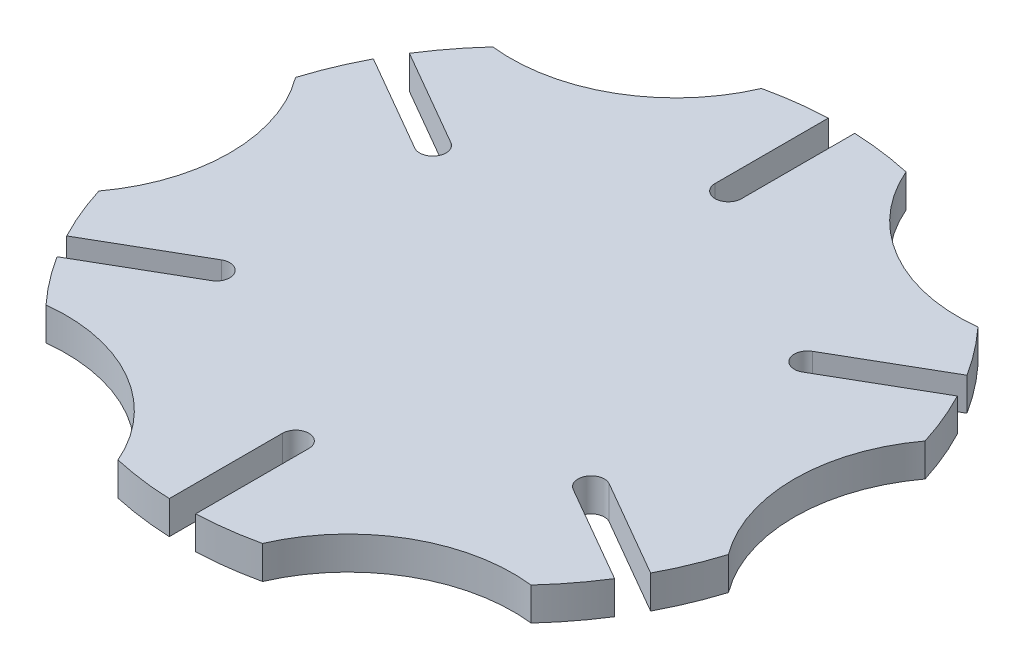
SolidWorks part; units mm, degrees
ref_plane "Front Plane" through (0, 0, 0) normal (0, 0, 1) x (1, 0, 0)
ref_plane "Top Plane" through (0, 0, 0) normal (0, 1, 0) x (1, 0, 0)
ref_plane "Right Plane" through (0, 0, 0) normal (1, 0, 0) x (0, 0, -1)
sketch "Sketch1" plane through (0, 0, 0) normal (0, 1, 0) x (1, 0, 0)
  line L0 (0, 0) -> (43.3013, 25) construction
  line L1 (43.3013, 25) -> (67.7962, 0) construction
  line L2 (67.7962, 0) -> (0, 0) construction
  line L3 (43.3013, 25) -> (28.4023, 16.3981) construction
  line L4 (44.3013, 23.2679) -> (29.4023, 14.666)
  line L5 (42.3013, 26.7321) -> (27.4023, 18.1301)
  line L6 (43.3013, -25) -> (28.4023, -16.3981) construction
  line L7 (42.3013, -26.7321) -> (27.4023, -18.1301)
  line L8 (44.3013, -23.2679) -> (29.4023, -14.666)
  line L9 (0, -50) -> (0, -32.7962) construction
  line L10 (-2, -50) -> (-2, -32.7962)
  line L11 (2, -50) -> (2, -32.7962)
  line L12 (-43.3013, -25) -> (-28.4023, -16.3981) construction
  line L13 (-44.3013, -23.2679) -> (-29.4023, -14.666)
  line L14 (-42.3013, -26.7321) -> (-27.4023, -18.1301)
  line L15 (-43.3013, 25) -> (-28.4023, 16.3981) construction
  line L16 (-42.3013, 26.7321) -> (-27.4023, 18.1301)
  line L17 (-44.3013, 23.2679) -> (-29.4023, 14.666)
  line L18 (0, 50) -> (0, 32.7962) construction
  line L19 (2, 50) -> (2, 32.7962)
  line L20 (-2, 50) -> (-2, 32.7962)
  circle A0 centre (67.7962, 0) radius 35
  circle A1 centre (0, 0) radius 32.7962 construction
  circle A2 centre (0, 0) radius 50
  arc A3 (44.3013, 23.2679) -> (42.3013, 26.7321) centre (43.3013, 25) ccw
  arc A4 (27.4023, 18.1301) -> (29.4023, 14.666) centre (28.4023, 16.3981) ccw
  circle A5 centre (67.7962, 0) radius 25
  arc A6 (48.0582, 14.8493) -> (48.0582, -14.8493) centre (67.7962, 0) cw
  arc A7 (48.0582, -14.8493) -> (48.0582, 14.8493) centre (0, 0) ccw
  circle A8 centre (33.8981, -58.7132) radius 25
  arc A9 (42.3013, -26.7321) -> (44.3013, -23.2679) centre (43.3013, -25) ccw
  arc A10 (29.4023, -14.666) -> (27.4023, -18.1301) centre (28.4023, -16.3981) ccw
  circle A11 centre (-33.8981, -58.7132) radius 25
  arc A12 (-2, -50) -> (2, -50) centre (0, -50) ccw
  arc A13 (2, -32.7962) -> (-2, -32.7962) centre (0, -32.7962) ccw
  circle A14 centre (-67.7962, 0) radius 25
  arc A15 (-44.3013, -23.2679) -> (-42.3013, -26.7321) centre (-43.3013, -25) ccw
  arc A16 (-27.4023, -18.1301) -> (-29.4023, -14.666) centre (-28.4023, -16.3981) ccw
  circle A17 centre (-33.8981, 58.7132) radius 25
  arc A18 (-42.3013, 26.7321) -> (-44.3013, 23.2679) centre (-43.3013, 25) ccw
  arc A19 (-29.4023, 14.666) -> (-27.4023, 18.1301) centre (-28.4023, 16.3981) ccw
  circle A20 centre (33.8981, 58.7132) radius 25
  arc A21 (2, 50) -> (-2, 50) centre (0, 50) ccw
  arc A22 (-2, 32.7962) -> (2, 32.7962) centre (0, 32.7962) ccw
  point P7 (35.8518, 20.699)
  point P16 (-44.2689, 68.1975)
  point P17 (0, 0)
  point P18 (0, 0)
  point P21 (35.8518, -20.699)
  point P30 (0, -41.3981)
  point P39 (-35.8518, -20.699)
  point P48 (-35.8518, 20.699)
  point P57 (0, 41.3981)
  point P64 (0, 0)
  dimension "D4" = 2
  dimension "D5" = 50
  dimension "D6" = 0.3
  dimension "D7" = 0.3
  dimension "D8" = 6
  dimension "D1" = 50
  dimension "D2" = 35
  dimension "D3" = 30
extrude "Boss-Extrude1" add sketch "Sketch1" along normal blind 5 contours A5 A2 L4 A0 L8 | A22 L20 A2 A17 L16 A19 L17 A14 L13 A16 L14 A11 L10 A13 L11 A8 L7 A10 L8 A0 L4 A4 L5 A20 L19
